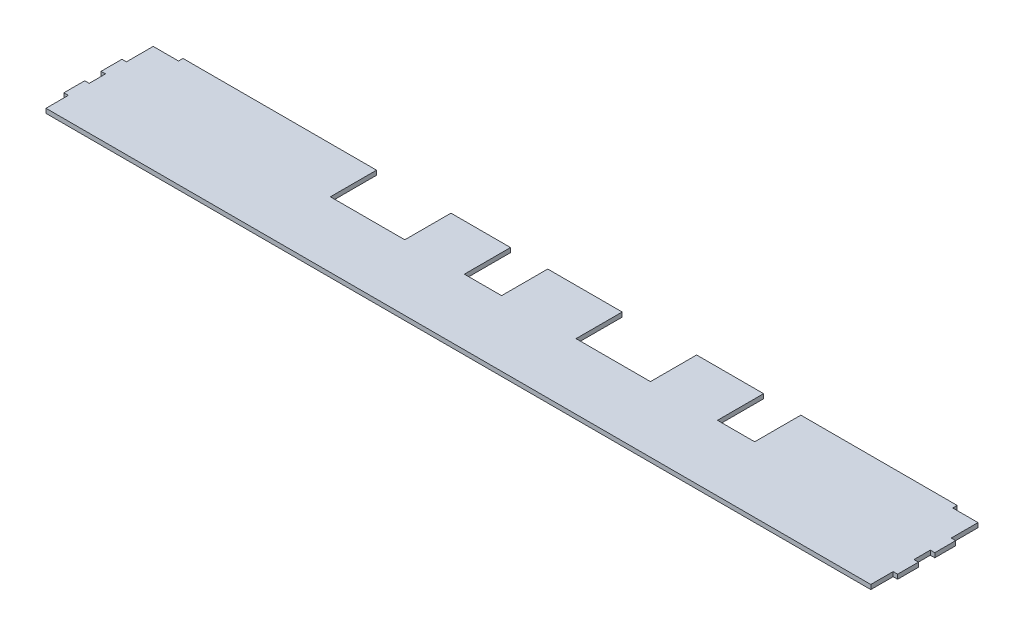
SolidWorks part; units mm, degrees
ref_plane "Front" through (0, 0, 0) normal (0, 0, 1) x (1, 0, 0)
ref_plane "Top" through (0, 0, 0) normal (0, 1, 0) x (1, 0, 0)
ref_plane "Right" through (0, 0, 0) normal (1, 0, 0) x (0, 0, -1)
sketch "Sketch1" plane through (0, 0, 0) normal (0, 1, 0) x (1, 0, 0)
  line L1 (-176.9442, 84.5175) -> (383.0558, 84.5175)
  line L2 (-176.9442, 84.5175) -> (-176.9442, 9.5175)
  line L3 (-176.9442, 9.5175) -> (383.0558, 9.5175)
  line L4 (383.0558, 84.5175) -> (383.0558, 9.5175)
  dimension "D1" = 560
  dimension "D2" = 75
extrude "Boss-Extrude1" add sketch "Sketch1" along normal blind 3 contours L2 L1 L4 L3
sketch "Sketch2" plane through (0, 3, 0) normal (0, 1, 0) x (1, 0, 0)
  line L0 (-176.9442, 84.5175) -> (383.0558, 84.5175) construction
  line L1 (-176.9442, 84.5175) -> (-156.9442, 84.5175)
  line L2 (-176.9442, 84.5175) -> (-176.9442, 53.5175)
  line L3 (-176.9442, 53.5175) -> (-156.9442, 53.5175)
  line L4 (-156.9442, 84.5175) -> (-156.9442, 53.5175)
  line L5 (-156.9442, 53.5175) -> (-26.9442, 53.5175)
  line L6 (-156.9442, 53.5175) -> (-156.9442, 84.5175)
  line L7 (-156.9442, 84.5175) -> (-26.9442, 84.5175)
  line L8 (-26.9442, 53.5175) -> (-26.9442, 84.5175)
  line L10 (-26.9442, 53.5175) -> (23.0558, 53.5175)
  line L11 (-26.9442, 53.5175) -> (-26.9442, 84.5175)
  line L12 (-26.9442, 84.5175) -> (23.0558, 84.5175)
  line L13 (23.0558, 53.5175) -> (23.0558, 84.5175)
  line L14 (23.0558, 53.5175) -> (63.0558, 53.5175)
  line L15 (23.0558, 53.5175) -> (23.0558, 84.5175)
  line L16 (23.0558, 84.5175) -> (63.0558, 84.5175)
  line L17 (63.0558, 53.5175) -> (63.0558, 84.5175)
  line L18 (63.0558, 53.5175) -> (88.0558, 53.5175)
  line L19 (63.0558, 53.5175) -> (63.0558, 84.5175)
  line L20 (63.0558, 84.5175) -> (88.0558, 84.5175)
  line L21 (88.0558, 53.5175) -> (88.0558, 84.5175)
  line L22 (88.0558, 53.5175) -> (138.0558, 53.5175)
  line L23 (88.0558, 53.5175) -> (88.0558, 84.5175)
  line L24 (88.0558, 84.5175) -> (138.0558, 84.5175)
  line L25 (138.0558, 53.5175) -> (138.0558, 84.5175)
  line L26 (138.0558, 53.5175) -> (188.0558, 53.5175)
  line L27 (138.0558, 53.5175) -> (138.0558, 84.5175)
  line L28 (138.0558, 84.5175) -> (188.0558, 84.5175)
  line L29 (188.0558, 53.5175) -> (188.0558, 84.5175)
  line L30 (188.0558, 53.5175) -> (233.0558, 53.5175)
  line L31 (188.0558, 53.5175) -> (188.0558, 84.5175)
  line L32 (188.0558, 84.5175) -> (233.0558, 84.5175)
  line L33 (233.0558, 53.5175) -> (233.0558, 84.5175)
  line L34 (233.0558, 53.5175) -> (258.0558, 53.5175)
  line L35 (233.0558, 53.5175) -> (233.0558, 84.5175)
  line L36 (233.0558, 84.5175) -> (258.0558, 84.5175)
  line L37 (258.0558, 53.5175) -> (258.0558, 84.5175)
  line L38 (258.0558, 53.5175) -> (383.0558, 53.5175)
  line L39 (258.0558, 53.5175) -> (258.0558, 84.5175)
  line L40 (258.0558, 84.5175) -> (383.0558, 84.5175)
  line L41 (383.0558, 53.5175) -> (383.0558, 84.5175)
  line M19 (383.0558, 84.5175) -> (-176.9442, 84.5175)
  dimension "D1" = 20
  dimension "D2" = 31
  dimension "D3" = 130
  dimension "D4" = 50
  dimension "D5" = 40
  dimension "D6" = 25
  dimension "D7" = 50
  dimension "D8" = 50
  dimension "D9" = 45
  dimension "D10" = 25
extrude "Cut-Extrude2" cut sketch "Sketch2" against normal blind 3 contours L10 L13 L8 M19 | L18 L21 L17 M19 | L26 L29 L25 M19 | L34 L37 L33 M19
sketch "Sketch3" plane through (0, 3, 0) normal (0, 1, 0) x (1, 0, 0)
  line L1 (-176.9442, 84.5175) -> (-156.9442, 84.5175)
  line L2 (-176.9442, 84.5175) -> (-176.9442, 81.5175)
  line L3 (-176.9442, 81.5175) -> (-156.9442, 81.5175)
  line L4 (-156.9442, 84.5175) -> (-156.9442, 81.5175)
  dimension "D1" = 3
  dimension "D2" = 20
extrude "Cut-Extrude3" cut sketch "Sketch3" against normal blind 3 contours L2 L1 L4 L3
sketch "Sketch4" plane through (0, 3, 0) normal (0, 1, 0) x (1, 0, 0)
  line L1 (-196.9442, 81.5175) -> (383.0558, 81.5175)
  line L2 (-196.9442, 81.5175) -> (-196.9442, 84.5175)
  line L3 (-196.9442, 84.5175) -> (383.0558, 84.5175)
  line L4 (383.0558, 81.5175) -> (383.0558, 84.5175)
  dimension "D1" = 580
  dimension "D2" = 3
sketch "Sketch7" plane through (0, 3, 0) normal (0, 1, 0) x (1, 0, 0)
  line L0 (383.0558, 84.5175) -> (383.0558, 9.5175) construction
  line L1 (383.0558, 84.5175) -> (363.0558, 84.5175)
  line L2 (383.0558, 84.5175) -> (383.0558, 81.5175)
  line L3 (383.0558, 81.5175) -> (363.0558, 81.5175)
  line L4 (363.0558, 84.5175) -> (363.0558, 81.5175)
  line L5 (383.0558, 9.5175) -> (380.0558, 9.5175)
  line L6 (383.0558, 9.5175) -> (383.0558, 24.5175)
  line L7 (383.0558, 24.5175) -> (380.0558, 24.5175)
  line L8 (380.0558, 9.5175) -> (380.0558, 24.5175)
  line L9 (380.0558, 49.5175) -> (383.0558, 49.5175)
  line L10 (380.0558, 49.5175) -> (380.0558, 38.5175)
  line L11 (380.0558, 38.5175) -> (383.0558, 38.5175)
  line L12 (383.0558, 49.5175) -> (383.0558, 38.5175)
  line L13 (-176.9442, 81.5175) -> (-176.9442, 9.5175) construction
  line L14 (380.0558, 81.5175) -> (383.0558, 81.5175)
  line L15 (380.0558, 81.5175) -> (380.0558, 63.5175)
  line L16 (380.0558, 63.5175) -> (383.0558, 63.5175)
  line L17 (383.0558, 81.5175) -> (383.0558, 63.5175)
  line L18 (-176.9442, 9.5175) -> (-173.9442, 9.5175)
  line L19 (-176.9442, 9.5175) -> (-176.9442, 24.5175)
  line L20 (-176.9442, 24.5175) -> (-173.9442, 24.5175)
  line L21 (-173.9442, 9.5175) -> (-173.9442, 24.5175)
  line L22 (-176.9442, 38.5175) -> (-173.9442, 38.5175)
  line L23 (-176.9442, 38.5175) -> (-176.9442, 49.5175)
  line L24 (-176.9442, 49.5175) -> (-173.9442, 49.5175)
  line L25 (-173.9442, 38.5175) -> (-173.9442, 49.5175)
  line L26 (-176.9442, 81.5175) -> (-156.9442, 81.5175) construction
  line L27 (-176.9442, 63.5175) -> (-173.9442, 63.5175)
  line L28 (-176.9442, 63.5175) -> (-176.9442, 81.5175)
  line L29 (-176.9442, 81.5175) -> (-173.9442, 81.5175)
  line L30 (-173.9442, 63.5175) -> (-173.9442, 81.5175)
  point P19 (381.5558, 24.5175)
  line M15 (-156.9442, 81.5175) -> (-176.9442, 81.5175)
  line M16 (-176.9442, 81.5175) -> (-176.9442, 9.5175)
  line M17 (-176.9442, 9.5175) -> (383.0558, 9.5175)
  line M18 (383.0558, 9.5175) -> (383.0558, 84.5175)
  line M19 (383.0558, 84.5175) -> (258.0558, 84.5175)
  dimension "D1" = 20
  dimension "D2" = 3
  dimension "D3" = 3
  dimension "D4" = 11
  dimension "D5" = 14
  dimension "D6" = 18
  dimension "D7" = 15
  dimension "D8" = 3
  dimension "D9" = 3
  dimension "D10" = 3
  dimension "D11" = 15
  dimension "D12" = 11
  dimension "D13" = 14
  dimension "D14" = 18
extrude "Cut-Extrude8" cut sketch "Sketch7" against normal blind 10 contours L21 L20 M17 M16 | L22 L25 L24 M16 | L27 L30 M15 M16 | L8 L7 M17 M18 | L10 L11 L9 M18 | L15 L16 L3 M18 | L4 L3 M19 M18
